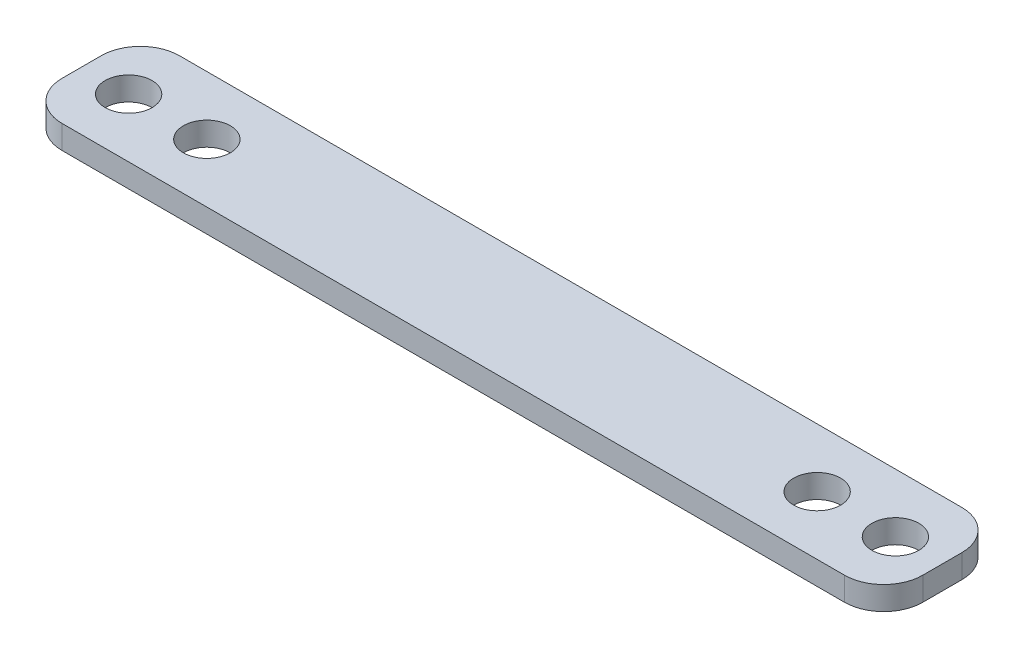
SolidWorks part; units mm, degrees
ref_plane "Front Plane" through (0, 0, 0) normal (0, 0, 1) x (1, 0, 0)
ref_plane "Top Plane" through (0, 0, 0) normal (0, 1, 0) x (1, 0, 0)
ref_plane "Right Plane" through (0, 0, 0) normal (1, 0, 0) x (0, 0, -1)
sketch "Sketch1" plane through (0, 0, 0) normal (0, 1, 0) x (1, 0, 0)
  line L1 (55, -7.5) -> (-55, -7.5)
  line L2 (55, -7.5) -> (55, 7.5)
  line L3 (55, 7.5) -> (-55, 7.5)
  line L4 (-55, -7.5) -> (-55, 7.5)
  line L5 (55, -7.5) -> (-55, 7.5) construction
  line L6 (55, 7.5) -> (-55, -7.5) construction
  point P0 (0, 0)
  dimension "D1" = 15
  dimension "D2" = 110
extrude "Boss-Extrude1" add sketch "Sketch1" along normal blind 3
sketch "Sketch2" plane through (0, 3, 0) normal (0, 1, 0) x (1, 0, 0)
  line L0 (-55, 0) -> (55, 0) construction
  line L1 (-55, 7.5) -> (-55, -7.5) construction
  line L2 (55, -7.5) -> (55, 7.5) construction
  circle A0 centre (-49, 0) radius 3
  circle A1 centre (-39, 0) radius 3
  dimension "D1" = 6
  dimension "D2" = 6
  dimension "D4" = 10
  dimension "D3" = 2
extrude "Cut-Extrude1" cut sketch "Sketch2" against normal up to next
mirror "Mirror1" about plane through (0, 0, 0) normal (1, 0, 0) of "Cut-Extrude1"
fillet "Fillet1" radius 5 4 edges at (55, 1.5, -7.5) (55, 1.5, 7.5) (-55, 1.5, 7.5) (-55, 1.5, -7.5)
